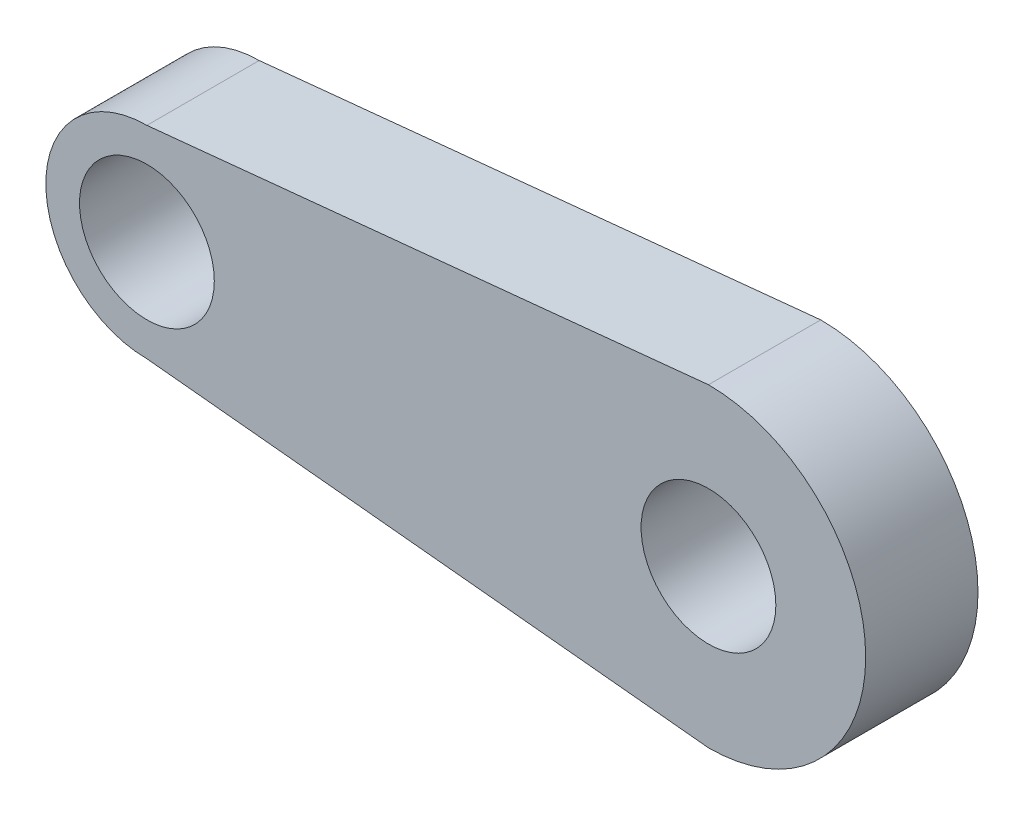
SolidWorks part; units mm, degrees
ref_plane "Front Plane" through (0, 0, 0) normal (0, 0, 1) x (1, 0, 0)
ref_plane "Top Plane" through (0, 0, 0) normal (0, 1, 0) x (1, 0, 0)
ref_plane "Right Plane" through (0, 0, 0) normal (1, 0, 0) x (0, 0, -1)
sketch "Sketch1" plane through (0, 0, 0) normal (0, 0, 1) x (1, 0, 0)
  line L0 (-25, 4.5) -> (0, 7)
  line L2 (-25, -4.5) -> (0, -7)
  circle A7 centre (0, 0) radius 3
  circle A8 centre (-25, 0) radius 3
  circle A9 centre (-25, 0) radius 4.5
  circle A10 centre (0, 0) radius 7
  point P2 (0, 0)
  dimension "D2" = 6
  dimension "D3" = 6
  dimension "D4" = 9
  dimension "D5" = 25
  dimension "D6" = 25
  dimension "D1" = 14
extrude "Boss-Extrude1" add sketch "Sketch1" along normal blind 5 contours A10 L0 A9 L2 | L0 A10 L2 A7 | A9 A8
